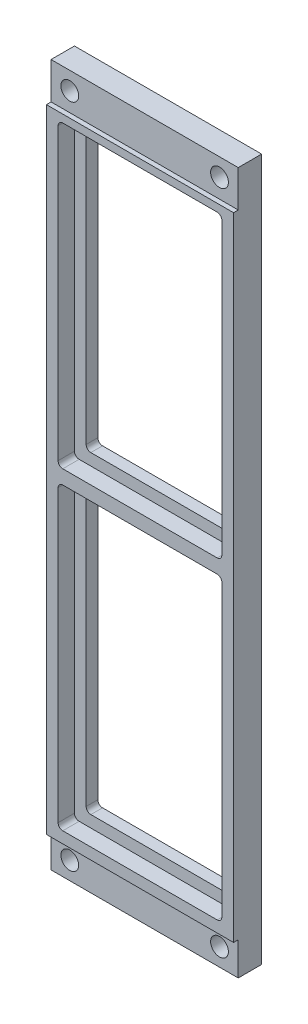
SolidWorks part; units mm, degrees
ref_plane "正面" through (0, 0, 0) normal (0, 0, 1) x (1, 0, 0)
ref_plane "平面" through (0, 0, 0) normal (0, 1, 0) x (1, 0, 0)
ref_plane "右側面" through (0, 0, 0) normal (1, 0, 0) x (0, 0, -1)
sketch "ｽｹｯﾁ1" plane through (0, 0, 0) normal (0, 0, 1) x (1, 0, 0)
  line L1 (0, 0) -> (40, 0)
  line L2 (0, 0) -> (0, 150)
  line L3 (0, 150) -> (40, 150)
  line L4 (40, 0) -> (40, 150)
  dimension "D1" = 150
  dimension "D2" = 40
extrude "ﾎﾞｽ - 押し出し1" add sketch "ｽｹｯﾁ1" along normal blind 6
sketch "ｽｹｯﾁ2" plane through (0, 0, 6) normal (0, 0, 1) x (1, 0, 0)
  line L0 (20, 150) -> (20, 0) construction
  line L1 (40, 150) -> (0, 150) construction
  line L2 (0, 0) -> (40, 0) construction
  line L3 (0, 3.8) -> (40, 3.8) construction
  line L4 (0, 150) -> (0, 0) construction
  line L5 (40, 0) -> (40, 150) construction
  line L6 (0, 146.2) -> (40, 146.2) construction
  circle A0 centre (36, 146.2) radius 1.9
  circle A1 centre (4, 146.2) radius 1.9
  circle A2 centre (4, 3.8) radius 1.9
  circle A3 centre (36, 3.8) radius 1.9
  dimension "D3" = 3.8
  dimension "D1" = 3.8
  dimension "D2" = 3.8
  dimension "D4" = 16
  dimension "D5" = 16
  dimension "D6" = 16
  dimension "D7" = 16
extrude "ｶｯﾄ - 押し出し1" cut sketch "ｽｹｯﾁ2" against normal through all
sketch "ｽｹｯﾁ3" plane through (0, 0, 6) normal (0, 0, 1) x (1, 0, 0)
  line L0 (20, 150) -> (20, 0) construction
  line L1 (40, 150) -> (0, 150) construction
  line L2 (0, 0) -> (40, 0) construction
  line L3 (0, 75) -> (40, 75) construction
  line L4 (0, 150) -> (0, 0) construction
  line L5 (40, 0) -> (40, 150) construction
  line L7 (5, 138) -> (35, 138)
  line L8 (5, 138) -> (5, 79)
  line L9 (5, 79) -> (35, 79)
  line L10 (35, 138) -> (35, 79)
  line L11 (5, 138) -> (35, 79) construction
  line L12 (5, 79) -> (35, 138) construction
  line L13 (5, 71) -> (35, 71)
  line L14 (5, 71) -> (5, 12)
  line L15 (5, 12) -> (35, 12)
  line L16 (35, 71) -> (35, 12)
  line L17 (5, 71) -> (35, 12) construction
  line L18 (5, 12) -> (35, 71) construction
  point P12 (20, 108.5)
  point P17 (20, 41.5)
  dimension "D1" = 4
  dimension "D2" = 4
  dimension "D3" = 12
  dimension "D4" = 12
  dimension "D5" = 30
extrude "ｶｯﾄ - 押し出し2" cut sketch "ｽｹｯﾁ3" against normal through all
sketch "ｽｹｯﾁ4" plane through (0, 0, 6) normal (0, 0, 1) x (1, 0, 0)
  line L0 (35, 138) -> (5, 138) construction
  line L3 (2.5, 140.5) -> (37.5, 140.5)
  line L6 (2.5, 140.5) -> (2.5, 76.5)
  line L11 (2.5, 76.5) -> (37.5, 76.5)
  line L12 (37.5, 140.5) -> (37.5, 76.5)
  line L17 (2.5, 73.5) -> (37.5, 73.5)
  line L18 (2.5, 73.5) -> (2.5, 9.5)
  line L19 (2.5, 9.5) -> (37.5, 9.5)
  line L20 (37.5, 73.5) -> (37.5, 9.5)
  line L21 (40, 0) -> (40, 150) construction
  line L22 (0, 150) -> (0, 0) construction
  line L24 (5, 79) -> (35, 79) construction
  line L25 (35, 71) -> (5, 71) construction
  line L26 (35, 12) -> (35, 71) construction
  line L27 (5, 12) -> (35, 12) construction
  dimension "D1" = 2.5
  dimension "D2" = 2.5
  dimension "D3" = 2.5
  dimension "D4" = 2.5
  dimension "D5" = 2.5
  dimension "D6" = 2.5
  dimension "D7" = 2.5
  dimension "D8" = 2.5
extrude "ｶｯﾄ - 押し出し3" cut sketch "ｽｹｯﾁ4" against normal blind 3.5
sketch "ｽｹｯﾁ5" plane through (0, 0, 6) normal (0, 0, 1) x (1, 0, 0)
  line L0 (0, 150) -> (0, 0) construction
  line L1 (0, 7.0782) -> (40, 7.0782)
  line L2 (0, 7.0782) -> (0, 0)
  line L3 (0, 0) -> (40, 0)
  line L4 (40, 7.0782) -> (40, 0)
  line L5 (40, 0) -> (40, 150) construction
  line L7 (0, 150) -> (40, 150)
  line L8 (0, 150) -> (0, 142.15)
  line L9 (0, 142.15) -> (40, 142.15)
  line L10 (40, 150) -> (40, 142.15)
  line L11 (4, 146.2) -> (36.3714, 146.2) construction
  line L14 (0, 0) -> (40, 0) construction
  line L15 (40, 150) -> (0, 150) construction
  dimension "D1" = 4.05
extrude "ｶｯﾄ - 押し出し4" cut sketch "ｽｹｯﾁ5" against normal blind 1
fillet "ﾌｨﾚｯﾄ1" radius 1 16 edges at (37.5, 140.5, 4.25) (2.5, 140.5, 4.25) (35, 79, 1.25) (37.5, 76.5, 4.25) (2.5, 76.5, 4.25) (5, 79, 1.25) (37.5, 73.5, 4.25) (2.5, 73.5, 4.25) (2.5, 9.5, 4.25) (37.5, 9.5, 4.25) (35, 12, 1.25) (5, 12, 1.25) (5, 71, 1.25) (35, 71, 1.25) (35, 138, 1.25) (5, 138, 1.25)
